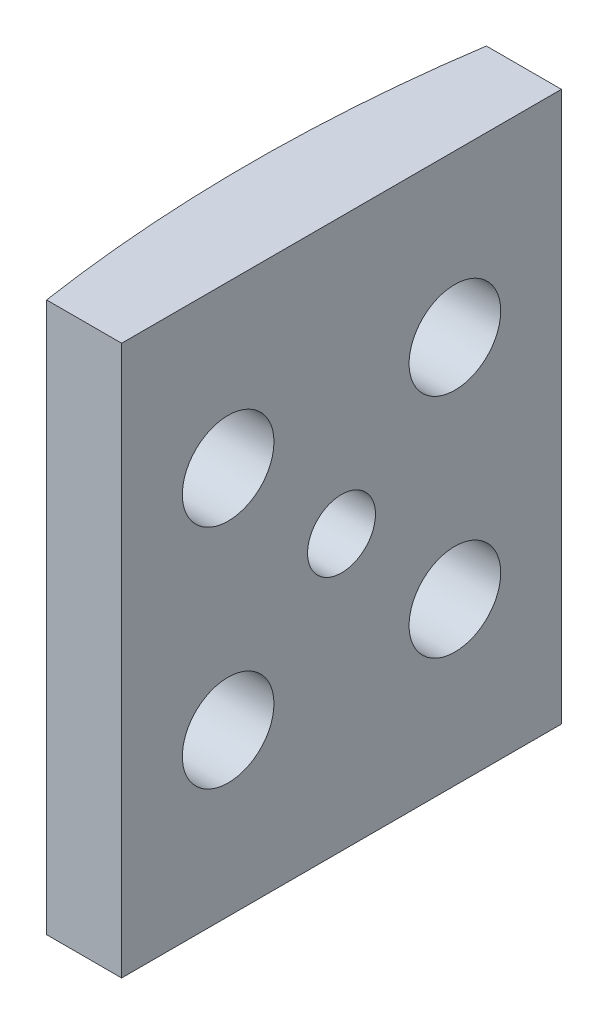
SolidWorks part; units mm, degrees
ref_plane "Front Plane" through (0, 0, 0) normal (0, 0, 1) x (1, 0, 0)
ref_plane "Top Plane" through (0, 0, 0) normal (0, 1, 0) x (1, 0, 0)
ref_plane "Right Plane" through (0, 0, 0) normal (1, 0, 0) x (0, 0, -1)
sketch "Sketch1" plane through (0, 0, 0) normal (0, 1, 0) x (1, 0, 0)
  line L0 (0, 0) -> (-180.5393, 0) construction
  line L1 (-79.0949, 12) -> (-75, 12)
  line L2 (-75, 12) -> (-75, -12)
  line L3 (-79.0949, -12) -> (-75, -12)
  arc A0 (-79.0949, 12) -> (-79.0949, -12) centre (0, 0) ccw
  point P6 (-80, 0)
  point P9 (-75, 0)
  dimension "D2" = 80
  dimension "D1" = 5
  dimension "D3" = 12
extrude "Boss-Extrude1" add sketch "Sketch1" along normal blind 30
sketch "Sketch2" plane through (-75, 0, 0) normal (1, 0, 0) x (0, 0, -1)
  line L0 (-12, 30) -> (12, 0) construction
  line L1 (0, 15) -> (6.1872, 21.1872) construction
  line L2 (12, 30) -> (12, 0) construction
  circle A0 centre (0, 15) radius 1.8536
  circle A1 centre (6.1872, 21.1872) radius 2.5
  circle A2 centre (6.1872, 8.8128) radius 2.5
  circle A3 centre (-6.1872, 8.8128) radius 2.5
  circle A4 centre (-6.1872, 21.1872) radius 2.5
  point P17 (0, 15)
  dimension "D2" = 5
  dimension "D3" = 8.75
  dimension "D4" = 45
  dimension "D1" = 4
extrude "Cut-Extrude1" cut sketch "Sketch2" against normal blind 18
